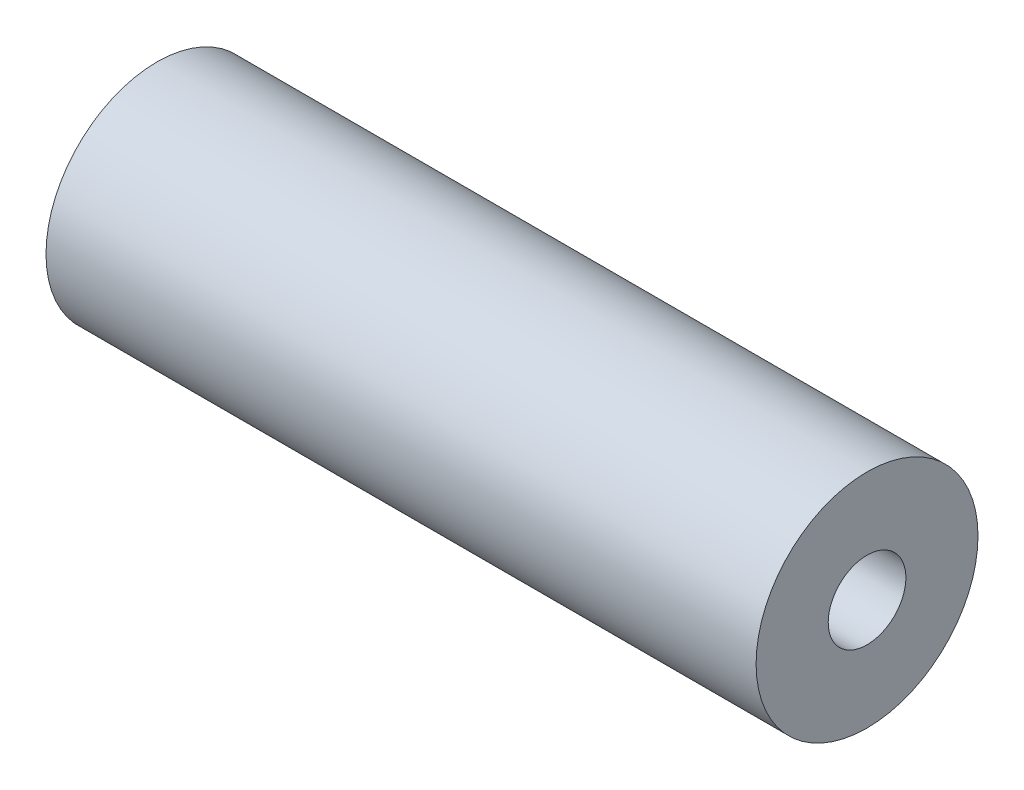
SolidWorks part; units mm, degrees
material "Lega 1060"
ref_plane "Piano frontale" through (0, 0, 0) normal (0, 0, 1) x (1, 0, 0)
ref_plane "Piano superiore" through (0, 0, 0) normal (0, 1, 0) x (1, 0, 0)
ref_plane "Piano destro" through (0, 0, 0) normal (1, 0, 0) x (0, 0, -1)
sketch "Schizzo1" plane through (0, 0, 0) normal (0, 0, 1) x (1, 0, 0)
  line L0 (0, 0) -> (57.8929, 0) construction
  line L1 (0, 5) -> (0, 1.75)
  line L2 (0, 1.75) -> (32, 1.75)
  line L3 (32, 1.75) -> (32, 5)
  line L4 (0, 5) -> (32, 5)
  dimension "D1" = 32
  dimension "D2" = 10
  dimension "D3" = 3.5
revolve "Rivoluzione1" add sketch "Schizzo1" angle 360 about L0
